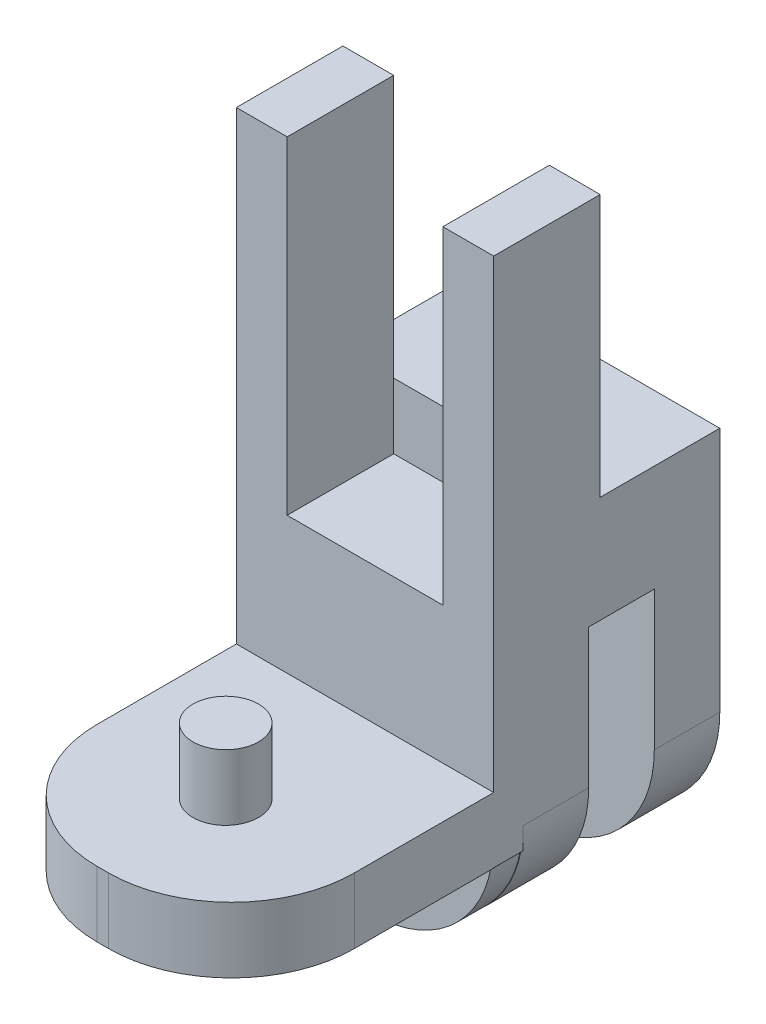
SolidWorks part; units mm, degrees
ref_plane "Front Plane" through (0, 0, 0) normal (0, 0, 1) x (1, 0, 0)
ref_plane "Top Plane" through (0, 0, 0) normal (0, 1, 0) x (1, 0, 0)
ref_plane "Right Plane" through (0, 0, 0) normal (1, 0, 0) x (0, 0, -1)
sketch "Sketch4" plane through (0, 0, 0) normal (0, 0, 1) x (1, 0, 0)
  line L0 (0, 82.063) -> (0, -112.4411) construction
  line L1 (-144.2959, 0) -> (145.5617, 0) construction
  line L2 (-12.7, 12.7) -> (-12.7, -12.7)
  line L3 (-15.7, 15.7) -> (15.7, 15.7)
  line L4 (-15.7, 15.7) -> (-15.7, -15.7)
  line L5 (-15.7, -15.7) -> (15.7, -15.7)
  line L6 (15.7, 15.7) -> (15.7, -15.7)
  line L7 (-12.7, -12.7) -> (12.7, -12.7)
  line L8 (12.7, 12.7) -> (12.7, -12.7)
  line L9 (-12.7, 12.7) -> (12.7, 12.7)
  dimension "D2" = 12.7
  dimension "D3" = 12.7
  dimension "D4" = 12.7
  dimension "D5" = 12.7
  dimension "D1" = 3
extrude "Boss-Extrude3" add sketch "Sketch4" along normal blind 30
sketch "Sketch5" plane through (0, 0, 30) normal (0, 0, 1) x (1, 0, 0)
  line L0 (-15.7, 15.7) -> (15.7, 15.7)
  line L1 (15.7, 15.7) -> (15.7, -15.7)
  line L2 (15.7, -15.7) -> (-15.7, -15.7)
  line L3 (-15.7, -15.7) -> (-15.7, 15.7)
extrude "Boss-Extrude4" add sketch "Sketch5" along normal blind 5
sketch "Sketch6" plane through (0, 0, 35) normal (0, 0, 1) x (1, 0, 0)
  line L0 (-14.6567, 0) -> (15.7, 0) construction
  line L1 (15.7, -15.7) -> (15.7, 15.7) construction
  line L2 (-15.7, 4) -> (15.7, 4)
  line L3 (-15.7, 15.7) -> (-15.7, -15.7) construction
  line L4 (15.7, 4) -> (15.7, -4)
  line L5 (15.7, -4) -> (-15.7, -4)
  line L6 (-15.7, -4) -> (-15.7, 4)
  dimension "D1" = 4
  dimension "D2" = 4
extrude "Boss-Extrude5" add sketch "Sketch6" along normal blind 5
sketch "Sketch7" plane through (0, -4, 0) normal (0, -1, 0) x (1, 0, 0)
  line L0 (-15.7, 40) -> (-15.7, 52)
  line L1 (-0.7, 67) -> (0.7, 67)
  line L2 (15.7, 52) -> (15.7, 40)
  line L3 (-15.7, 40) -> (15.7, 40) construction
  line L4 (15.7, 40) -> (-15.7, 40)
  line L5 (0, 0) -> (0, 92.3619) construction
  arc A0 (0.7, 67) -> (15.7, 52) centre (0.7, 52) cw
  arc A1 (-15.7, 52) -> (-0.7, 67) centre (-0.7, 52) cw
  point P9 (15.7, 67)
  point P12 (-15.7, 67)
  dimension "D3" = 15
  dimension "D1" = 27
  dimension "D2" = 31.4
extrude "Boss-Extrude6" add sketch "Sketch7" against normal blind 8
sketch "Sketch8" plane through (0, -4, 0) normal (0, -1, 0) x (1, 0, 0)
  line L0 (0, 67.4318) -> (0, -5.9603) construction
  line L1 (0.7, 67) -> (-0.7, 67) construction
  circle A0 centre (0, 52) radius 4
  dimension "D1" = 15
extrude "Boss-Extrude7" add sketch "Sketch8" along normal blind 8
mirror "Mirror1" about plane through (0, 0, 0) normal (0, 1, 0) of "Boss-Extrude7"
sketch "Sketch9" plane through (0, 15.7, 0) normal (0, 1, 0) x (1, 0, 0)
  line L1 (-15.7, -32) -> (15.7, -32)
  line L2 (-15.7, -35) -> (-15.7, 0) construction
  line L3 (15.7, -35) -> (15.7, 0) construction
  line L4 (0, 15.8647) -> (0, -78.6922) construction
  line L5 (0, -52) -> (31.7707, -52) construction
  line L6 (31.7707, -52) -> (-30.9902, -52) construction
  line L7 (-15.7, -32) -> (-15.7, -22)
  line L8 (-15.7, -22) -> (15.7, -22)
  line L9 (15.7, -22) -> (15.7, -32)
  dimension "D1" = 20
  dimension "D2" = 10
extrude "Boss-Extrude8" add sketch "Sketch9" along normal blind 5
sketch "Sketch10" plane through (0, 15.7, 0) normal (0, 1, 0) x (1, 0, 0)
  line L0 (-15.7, -22) -> (-15.7, -12)
  line L1 (-15.7, -22) -> (-15.7, 0) construction
  line L2 (-15.7, -12) -> (15.7, -12)
  line L3 (15.7, -22) -> (15.7, 0) construction
  line L4 (15.7, -12) -> (15.7, -22)
  line L5 (15.7, -22) -> (-15.7, -22)
  dimension "D1" = 10
extrude "Boss-Extrude9" add sketch "Sketch10" along normal blind 13
sketch "Sketch11" plane through (0, 20.7, 0) normal (0, 1, 0) x (1, 0, 0)
  line L0 (-15.7, -22) -> (-9.5, -22)
  line L1 (15.7, -22) -> (-15.7, -22) construction
  line L2 (-9.5, -22) -> (-9.5, -32)
  line L3 (-15.7, -32) -> (15.7, -32) construction
  line L4 (-9.5, -32) -> (-15.7, -32)
  line L5 (-15.7, -32) -> (-15.7, -22)
  line L6 (9.5, -22) -> (9.5, -32)
  line L7 (-15.7, -22) -> (15.7, -22) construction
  line L8 (-15.7, -32) -> (15.7, -32) construction
  line L9 (9.5, -32) -> (15.7, -32)
  line L10 (15.7, -32) -> (15.7, -22)
  line L11 (15.7, -32) -> (15.7, -22) construction
  line L12 (15.7, -22) -> (9.5, -22)
  dimension "D1" = 6.2
  dimension "D2" = 6.2
extrude "Boss-Extrude10" add sketch "Sketch11" along normal blind 40
sketch "Sketch12" plane through (0, 0, 32) normal (0, 0, 1) x (1, 0, 0)
  line L0 (-15.7, 60.7) -> (-9.5, 60.7)
  line L1 (-9.5, 60.7) -> (-9.5, 20.7)
  line L2 (-9.5, 20.7) -> (9.5, 20.7)
  line L3 (9.5, 20.7) -> (9.5, 60.7)
  line L4 (9.5, 60.7) -> (15.7, 60.7)
  line L5 (15.7, 60.7) -> (15.7, 15.7)
  line L6 (15.7, 15.7) -> (-15.7, 15.7)
  line L7 (-15.7, 15.7) -> (-15.7, 60.7)
extrude "Boss-Extrude11" add sketch "Sketch12" along normal blind 3
sketch "Sketch13" plane through (-15.7, 0, 0) normal (-1, 0, 0) x (0, 0, 1)
  line L5 (0, 15.7) -> (31.4, 15.7)
  line L6 (31.4, 15.7) -> (31.4, -15.7)
  line L7 (35, -15.7) -> (0, -15.7) construction
  line L8 (31.4, -15.7) -> (0, -15.7)
  line L9 (0, -15.7) -> (0, 15.7)
  dimension "D1" = 31.4
extrude "Cut-Extrude1" cut sketch "Sketch13" against normal blind 31.4
sketch "Sketch15" plane through (0, 0, 31.4) normal (0, 0, -1) x (-1, 0, 0)
  line L1 (15.7, -1.3) -> (15.7, 15.7)
  line L2 (15.7, 15.7) -> (-15.7, 15.7)
  line L5 (-15.7, 15.7) -> (-15.7, -1.3)
  line L6 (-0.7, -16.3) -> (0.7, -16.3)
  arc A2 (15.7, -1.3) -> (0.7, -16.3) centre (0.7, -1.3) cw
  arc A3 (-15.7, -1.3) -> (-0.7, -16.3) centre (-0.7, -1.3) ccw
  circle A4 centre (0, -1.3) radius 4
  point P12 (15.7, -15.7)
  point P15 (-15.7, -15.7)
  point P16 (15.7, -16.3)
  dimension "D1" = 32
  dimension "D2" = 15
  dimension "D3" = 15
extrude "Boss-Extrude12" add sketch "Sketch15" along normal blind 8
ref_plane "Plane1" through (0, 0, 19.4) normal (0, 0, -1) x (-1, 0, 0)
mirror "Mirror2" about plane through (0, 0, 19.4) normal (0, 0, -1) of "Boss-Extrude12"
sketch "Sketch16" plane through (0, 0, 12) normal (0, 0, -1) x (-1, 0, 0)
  line L0 (-15.7, 28.7) -> (15.7, 28.7)
  line L1 (15.7, 28.7) -> (15.7, 15.7)
  line L2 (15.7, 15.7) -> (-15.7, 15.7)
  line L3 (-15.7, 15.7) -> (-15.7, 28.7)
extrude "Boss-Extrude13" add sketch "Sketch16" along normal blind 4.6
sketch "Sketch17" plane through (0, -15.7, 0) normal (0, -1, 0) x (1, 0, 0)
  line L0 (-15.7, 35) -> (15.7, 35)
  line L1 (15.7, 35) -> (15.7, 31.4)
  line L2 (15.7, 31.4) -> (-15.7, 31.4)
  line L3 (-15.7, 31.4) -> (-15.7, 35)
extrude "Boss-Extrude14" add sketch "Sketch17" along normal blind 0.6
sketch "Sketch24" plane through (0, 0, 31.4) normal (0, 0, -1) x (-1, 0, 0)
  line L0 (-15.7, -3.9559) -> (-15.7, -16.3)
  line L1 (-15.7, -16.3) -> (-15.7, -1.3) construction
  line L2 (-15.7, -16.3) -> (-0.7, -16.3)
  line L3 (-15.4, -3.9448) -> (-15.7, -3.9559)
  arc A0 (-0.7, -16.3) -> (-15.4, -3.9448) centre (-0.7, -1.3775) cw
extrude "Cut-Extrude2" cut sketch "Sketch24" against normal blind 3.6
mirror "Mirror3" about plane through (0, 0, 0) normal (1, 0, 0) of "Cut-Extrude2"
